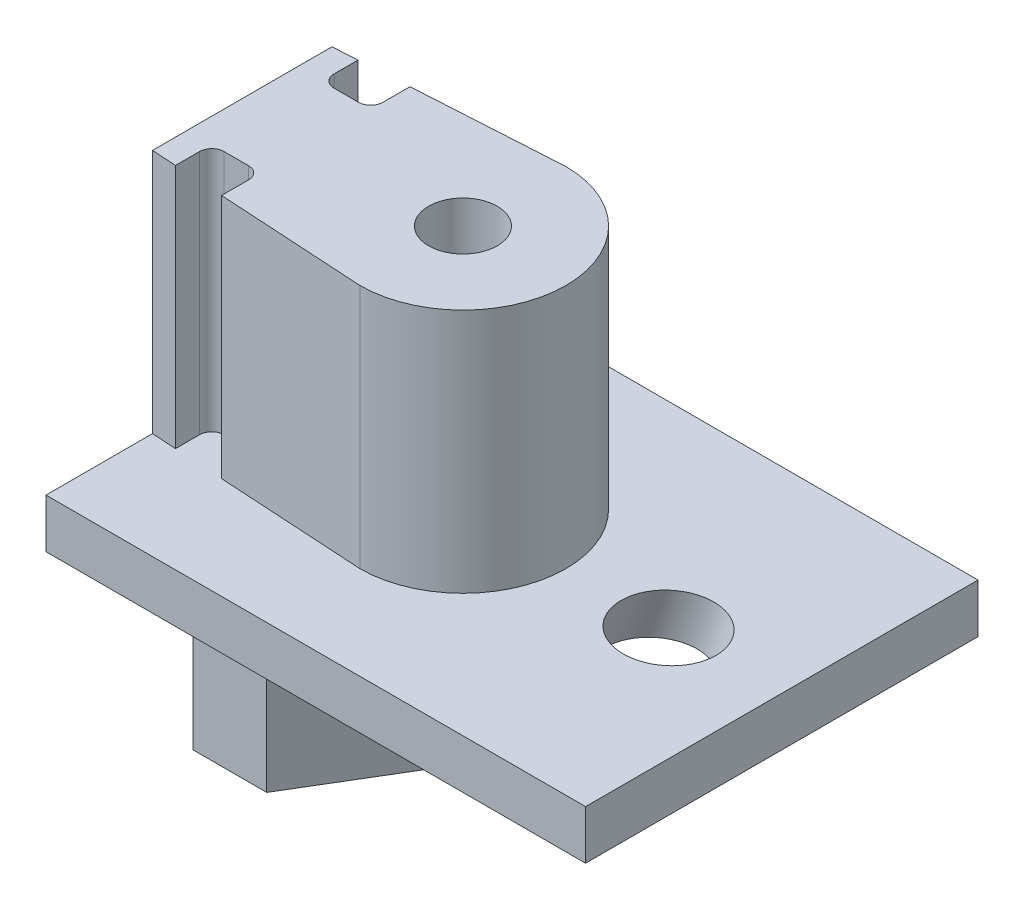
SolidWorks part; units mm, degrees
ref_plane "Front Plane" through (0, 0, 0) normal (0, 0, 1) x (1, 0, 0)
ref_plane "Top Plane" through (0, 0, 0) normal (0, 1, 0) x (1, 0, 0)
ref_plane "Right Plane" through (0, 0, 0) normal (1, 0, 0) x (0, 0, -1)
sketch "Sketch3" plane through (0, 0, 0) normal (0, 1, 0) x (1, 0, 0)
  line L0 (-5, 0.75) -> (0, 1.05) construction
  line L3 (0, -1.05) -> (-5, -0.75) construction
  line L4 (-2.5, 0.9) -> (-2, 0.93)
  line L6 (-4.25, 0) -> (-5.75, 0) construction
  line L7 (-2, 0.93) -> (-2, 0.56)
  line L8 (-2.5, 0.9) -> (-5, 0.9) construction
  line L9 (-2.5, 0.9) -> (-2.5, -0.9)
  line L10 (-2.5, -0.9) -> (-5, -0.9) construction
  line L11 (-5, 0.9) -> (-5, -0.9) construction
  line L12 (-2, 0.96) -> (-1.5, 0.96) construction
  line L13 (-2, 0.96) -> (-2, 0.56) construction
  line L14 (-2, 0.56) -> (-1.5, 0.56)
  line L15 (-1.5, 0.96) -> (-1.5, 0.56)
  line L16 (-1.5, -0.56) -> (-2, -0.56)
  line L17 (-1.5, -0.56) -> (-1.5, -0.96)
  line L18 (-1.5, -0.96) -> (-2, -0.96) construction
  line L19 (-2, -0.56) -> (-2, -0.96) construction
  line L21 (-2.5, -0.9) -> (-2, -0.93)
  line L22 (-2, -0.93) -> (-2, -0.56)
  line L23 (-1.5, 0.96) -> (0, 1.05)
  line L24 (0, -1.05) -> (-1.5, -0.96)
  circle A2 centre (0, 0) radius 0.6 construction
  circle A3 centre (0, 0) radius 0.4 construction
  circle A4 centre (-5, 0) radius 0.35 construction
  circle A5 centre (0, 0) radius 1.05 construction
  circle A6 centre (-5, 0) radius 0.75 construction
  arc A7 (-5, 0.9) -> (-5, -0.9) centre (-5, 0) ccw construction
  arc A8 (0, 1.05) -> (0, -1.05) centre (0, 0) cw
  point P4 (-2, -0.93)
  point P15 (-5, 0)
  point P16 (-2, 0.93)
  point P22 (-5, 0)
  dimension "D2" = 1.2
  dimension "D3" = 0.8
  dimension "D4" = 0.7
  dimension "D6" = 5
  dimension "D1" = 1.5
  dimension "D5" = 2.1
  dimension "D7" = 0.4
  dimension "D9" = 2.5
  dimension "D10" = 1.8
  dimension "D11" = 2.5
  dimension "D12" = 0.5
  dimension "D14" = 1.5
extrude "Boss-Extrude1" add sketch "Sketch3" along normal blind 2.5 contours L21 L22 L16 L17 L24 A8 L23 L15 L14 L7 L4 L9
sketch "Sketch4" plane through (0, 2.5, 0) normal (0, 1, 0) x (1, 0, 0)
  circle A0 centre (0, 0) radius 0.35
  point P9 (0, 0)
  dimension "D1" = 0.7
extrude "Through Holes" cut sketch "Sketch4" against normal through all contours A0
fillet "Fillet1" radius 0.125 4 edges at (-2, 1.25, 0.56) (-1.5, 1.25, 0.56) (-1.5, 1.25, -0.56) (-2, 1.25, -0.56)
sketch "Sketch5" plane through (0, 0, 0) normal (0, 1, 0) x (1, 0, 0)
  line L0 (-2.25, 0) -> (1.75, 0) construction
  line L1 (-2.25, -2) -> (1.75, -2)
  line L2 (-2.25, -2) -> (-2.25, 2)
  line L3 (-2.25, 2) -> (1.75, 2)
  line L4 (1.75, -2) -> (1.75, 2) construction
  line L5 (-2.25, -2) -> (1.75, 2) construction
  line L6 (-2.25, 2) -> (1.75, -2) construction
  line L8 (1.75, 2) -> (3.25, 2)
  line L9 (3.25, 2) -> (3.25, -2)
  line L10 (3.25, -2) -> (1.75, -2)
  circle A1 centre (0, 0) radius 0.125
  point P1 (-0.25, 0)
  dimension "D2" = 0.25
  dimension "D1" = 1.75
  dimension "D3" = 4
  dimension "D4" = 1.5
  dimension "D5" = 4
extrude "Boss-Extrude2" add sketch "Sketch5" against normal blind 0.5
sketch "Sketch6" plane through (0, 0, 0) normal (0, 0, 1) x (1, 0, 0)
  line L0 (3.25, 0) -> (3.25, 1.25)
  line L1 (3.25, 1.25) -> (1.75, 1.75)
  line L2 (1.75, 1.75) -> (1.75, 0)
  line L3 (1.75, 0) -> (3.25, 0)
  line L4 (2.5, 1.5) -> (1.6412, -1.0764)
  dimension "D1" = 1.25
  dimension "D2" = 1.75
ref_plane "Plane1" through (0.7, 2.1, 0) normal (0.3162, 0.9487, 0) x (0.9487, -0.3162, 0)
sketch "Sketch8" plane through (0.7, 2.1, 0) normal (0.3162, 0.9487, 0) x (0.9487, -0.3162, 0)
  line L0 (2.6879, 0) -> (1.1068, 0) construction
  line L2 (2.6879, 0) -> (1.9879, 0) construction
  circle A0 centre (1.9879, 0) radius 0.46
  dimension "D1" = 0.92
  dimension "D2" = 0.7
extrude "Cut-Extrude1" cut sketch "Sketch8" against normal through all
sketch "Sketch9" plane through (0, 0, 0) normal (0, -1, 0) x (1, 0, 0)
  line L0 (-2.25, 2) -> (-2.25, -2)
  line L1 (-2.25, -2) -> (-3.715, -2)
  line L2 (-3.715, -2) -> (-3.715, 2)
  line L3 (-3.715, 2) -> (-2.25, 2)
extrude "Cut-Extrude2" cut sketch "Sketch9" against normal through all both and the other way through all
sketch "Sketch10" plane through (0, -0.5, 0) normal (0, -1, 0) x (1, 0, 0)
  line L0 (-1.5, 1.25) -> (-1.5, -1.25)
  line L1 (-1.5, -1.25) -> (-0.75, -1.25)
  line L2 (-0.75, -1.25) -> (0, 0)
  line L3 (-2.25, 0) -> (1.75, 0) construction
  line L4 (0, 0) -> (-0.75, 1.25)
  line L5 (-0.75, 1.25) -> (-1.5, 1.25)
  line L6 (0, 0) -> (-1.5, 0) construction
  point P8 (-1.5, 0)
  dimension "D1" = 1.5
  dimension "D2" = 2.5
  dimension "D3" = 0.75
  dimension "D4" = 0.75
extrude "Boss-Extrude3" add sketch "Sketch10" along normal blind 1.75
